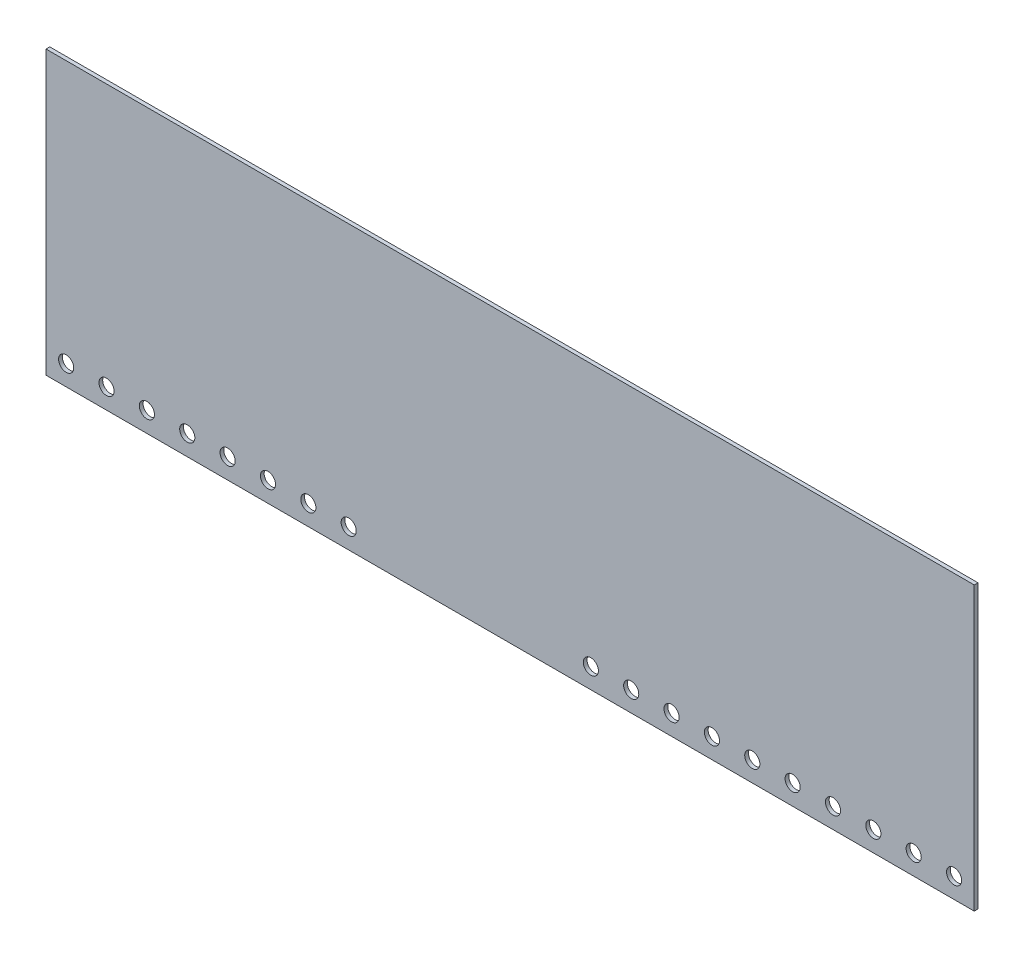
SolidWorks part; units mm, degrees
material "ABS PC"
ref_plane "Front Plane" through (0, 0, 0) normal (0, 0, 1) x (1, 0, 0)
ref_plane "Top Plane" through (0, 0, 0) normal (0, 1, 0) x (1, 0, 0)
ref_plane "Right Plane" through (0, 0, 0) normal (1, 0, 0) x (0, 0, -1)
sketch "Sketch1" plane through (0, 0, 0) normal (0, 0, 1) x (1, 0, 0)
  line L0 (-314.1795, -37.0941) -> (270.0205, -37.0941)
  line L1 (-314.1795, -37.0941) -> (-314.1795, 140.7059)
  line L2 (-314.1795, 140.7059) -> (270.0205, 140.7059)
  line L3 (270.0205, -37.0941) -> (270.0205, 140.7059)
  circle A0 centre (-301.4795, -24.3941) radius 4.7625
  circle A1 centre (-276.0795, -24.3941) radius 4.7625
  circle A2 centre (-250.6795, -24.3941) radius 4.7625
  circle A3 centre (-225.2795, -24.3941) radius 4.7625
  circle A4 centre (-199.8795, -24.3941) radius 4.7625
  circle A5 centre (-174.4795, -24.3941) radius 4.7625
  circle A6 centre (-149.0795, -24.3941) radius 4.7625
  circle A7 centre (-123.6795, -24.3941) radius 4.7625
  circle A8 centre (28.7205, -24.3941) radius 4.7625
  circle A9 centre (54.1205, -24.3941) radius 4.7625
  circle A10 centre (79.5205, -24.3941) radius 4.7625
  circle A11 centre (104.9205, -24.3941) radius 4.7625
  circle A12 centre (130.3205, -24.3941) radius 4.7625
  circle A13 centre (155.7205, -24.3941) radius 4.7625
  circle A14 centre (181.1205, -24.3941) radius 4.7625
  circle A15 centre (206.5205, -24.3941) radius 4.7625
  circle A16 centre (231.9205, -24.3941) radius 4.7625
  circle A17 centre (257.3205, -24.3941) radius 4.7625
  dimension "D4" = 12.7
  dimension "D1" = 177.8
  dimension "D2" = 584.2
  dimension "D3" = 12.7
extrude "Boss-Extrude1" add sketch "Sketch1" along normal mid plane 2.3622
